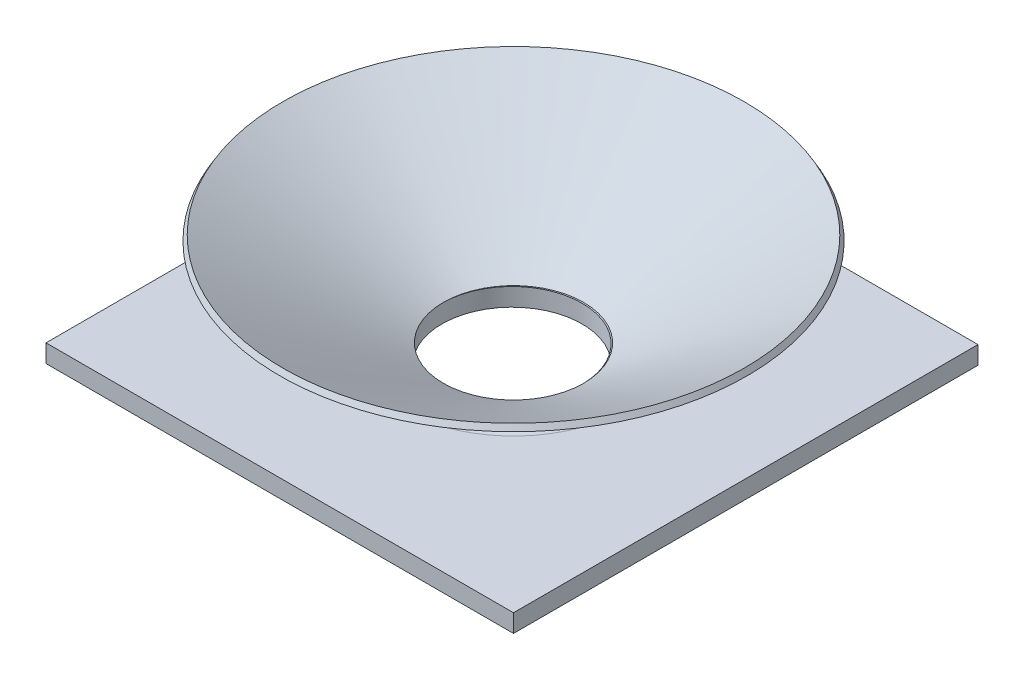
SolidWorks part; units mm, degrees
ref_plane "Front Plane" through (0, 0, 0) normal (0, 0, 1) x (1, 0, 0)
ref_plane "Top Plane" through (0, 0, 0) normal (0, 1, 0) x (1, 0, 0)
ref_plane "Right Plane" through (0, 0, 0) normal (1, 0, 0) x (0, 0, -1)
sketch "Sketch1" plane through (0, 0, 0) normal (0, 0, 1) x (1, 0, 0)
  line L0 (-13.7069, 0) -> (-39.075, 14.7607)
  line L1 (-39.075, 14.7607) -> (-38.5721, 15.625)
  line L2 (-38.5721, 15.625) -> (-11.7185, 0)
  line L3 (-13.7069, 0) -> (-11.7185, 0)
  line L4 (0, 0) -> (0, 38.049) construction
  line L5 (0, 0) -> (-37.9362, 0) construction
  dimension "D1" = 11.7185
  dimension "D2" = 39.075
  dimension "D3" = 1
  dimension "D4" = 15.625
revolve "Revolve1" add sketch "Sketch1" angle 360 about L4
sketch "Sketch2" plane through (0, 0, 0) normal (0, 1, 0) x (1, 0, 0)
  line L0 (-39.075, -39.075) -> (39.075, -39.075)
  line L1 (-39.075, -39.075) -> (-39.075, 38.5721)
  line L2 (39.075, -39.075) -> (39.075, 38.5721)
  line L3 (-39.075, 38.5721) -> (39.075, 38.5721)
  line L4 (-39.075, -39.075) -> (39.075, 38.5721) construction
  line L5 (39.075, -39.075) -> (-39.075, 38.5721) construction
  circle A0 centre (0, -0.2515) radius 11.72
  circle A1 centre (0, 0) radius 39.075 construction
  circle A2 centre (0, 0) radius 38.5721 construction
  point P1 (0, -0.2515)
  dimension "D1" = 23.44
extrude "Boss-Extrude1" add sketch "Sketch2" against normal blind 3 separate body
sketch "Sketch3" plane through (0, 0, 0) normal (0, 0, 1) x (1, 0, 0)
  line L0 (-39.075, 14.7607) -> (-13.7069, 0) construction
  line L1 (-39.075, 0) -> (39.075, 0) construction
  line L2 (-13.7069, 0) -> (-18.361, 2.708)
  line L3 (-19.0915, 0) -> (-13.7069, 0)
  line L4 (0, 0) -> (0, 7.4579) construction
  arc A0 (-18.361, 2.708) -> (-19.0915, 0) centre (-19.0915, 1.4525) cw
revolve "Revolve2" add sketch "Sketch3" angle 360 about L4
